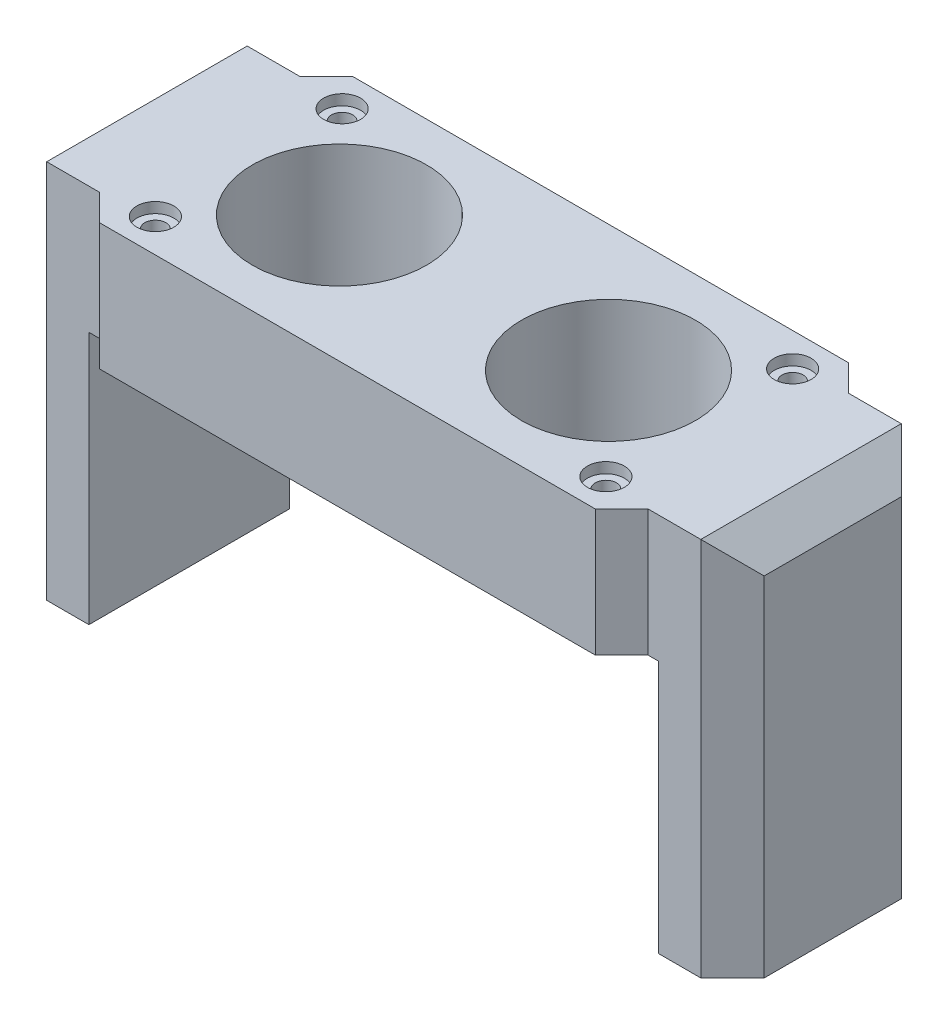
SolidWorks part; units mm, degrees
ref_plane "Front Plane" through (0, 0, 0) normal (0, 0, 1) x (1, 0, 0)
ref_plane "Top Plane" through (0, 0, 0) normal (0, 1, 0) x (1, 0, 0)
ref_plane "Right Plane" through (0, 0, 0) normal (1, 0, 0) x (0, 0, -1)
sketch "Sketch1" plane through (0, 0, 0) normal (0, 1, 0) x (1, 0, 0)
  line L0 (-12.75, 0) -> (12.75, 0) construction
  line L1 (-26, 12) -> (26, 12)
  line L2 (-26, 12) -> (-26, -12)
  line L3 (-26, -12) -> (26, -12)
  line L4 (26, 12) -> (26, -12)
  line L5 (-26, 12) -> (26, -12) construction
  line L6 (-26, -12) -> (26, 12) construction
  circle A0 centre (12.75, 0) radius 8.25
  circle A1 centre (-12.75, 0) radius 8.25
  point P0 (0, 0)
  point P9 (0, 0)
  dimension "D3" = 16.5
  dimension "D1" = 52
  dimension "D2" = 24
  dimension "D4" = 25.5
extrude "Boss-Extrude1" add sketch "Sketch1" along normal blind 12
sketch "Sketch2" plane through (0, 12, 0) normal (0, 1, 0) x (1, 0, 0)
  line L1 (-21.35, 8.85) -> (21.35, 8.85) construction
  line L2 (-21.35, 8.85) -> (-21.35, -8.85) construction
  line L3 (-21.35, -8.85) -> (21.35, -8.85) construction
  line L4 (21.35, 8.85) -> (21.35, -8.85) construction
  line L5 (-21.35, 8.85) -> (21.35, -8.85) construction
  line L6 (-21.35, -8.85) -> (21.35, 8.85) construction
  circle A0 centre (-21.35, 8.85) radius 1
  circle A1 centre (21.35, 8.85) radius 1
  circle A2 centre (21.35, -8.85) radius 1
  circle A3 centre (-21.35, -8.85) radius 1
  point P0 (0, 0)
  dimension "D3" = 2
  dimension "D1" = 17.7
  dimension "D2" = 42.7
extrude "Cut-Extrude1" cut sketch "Sketch2" against normal through all
sketch "Sketch3" plane through (0, 12, 0) normal (0, 1, 0) x (1, 0, 0)
  circle A20 centre (-21.35, 8.85) radius 1.75
  circle A21 centre (21.35, 8.85) radius 1.75
  circle A23 centre (21.35, -8.85) radius 1.75
  circle A24 centre (-21.35, -8.85) radius 1.75
  dimension "D1" = 3.5
extrude "Cut-Extrude2" cut sketch "Sketch3" against normal blind 1
sketch "Sketch4" plane through (0, 0, 0) normal (0, -1, 0) x (1, 0, 0)
  line L0 (26, -12) -> (-26, -12) construction
  line L1 (-6, -12) -> (6, -12)
  line L2 (-6, -12) -> (-6, -5)
  line L3 (-6, -5) -> (6, -5)
  line L4 (6, -12) -> (6, -5)
  line L5 (0, -5) -> (0, 0)
  line M14 (-26, -12) -> (26, -12)
  dimension "D1" = 7
  dimension "D2" = 12
extrude "Cut-Extrude3" cut sketch "Sketch4" against normal blind 5 contours L4 L3 L2 M14
fillet "Fillet3" radius 0.5 5 edges at (-6, 5, -8.5) (6, 5, -8.5) (6, 2.5, -5) (0, 5, -5) (-6, 2.5, -5)
chamfer "Chamfer1" distance 2.5 4 edges at (26, 6, 12) (26, 6, -12) (-26, 6, -12) (-26, 6, 12)
sketch "Sketch5" plane through (-26, 0, 0) normal (-1, 0, 0) x (0, 0, 1)
  line L4 (9.5, 12) -> (-9.5, 12)
  line L5 (-9.5, 12) -> (-9.5, 0)
  line L6 (-9.5, 0) -> (9.5, 0)
  line L7 (9.5, 0) -> (9.5, 12)
  line L8 (9.5, 12) -> (-9.5, 12)
  line L9 (-9.5, 12) -> (-9.5, 0)
  line L10 (-9.5, 0) -> (9.5, 0)
  line L11 (9.5, 0) -> (9.5, 12)
  dimension "D1" = 0
extrude "Boss-Extrude2" add sketch "Sketch5" along normal blind 8
sketch "Sketch6" plane through (0, 0, 0) normal (0, -1, 0) x (1, 0, 0)
  line L0 (-34, 9.5) -> (-34, -9.5)
  line L1 (-34, 9.5) -> (-26, 9.5) construction
  line L2 (-34, -9.5) -> (-34, 9.5) construction
  line L3 (-34, -9.5) -> (-27, -9.5)
  line L4 (-34, -9.5) -> (-26, -9.5) construction
  line L5 (-27, -9.5) -> (-27, 9.5)
  line L6 (-27, 9.5) -> (-34, 9.5)
  dimension "D1" = 7
extrude "Boss-Extrude3" add sketch "Sketch6" along normal blind 24 contours L6 L0 L3 L5
chamfer "Chamfer2" distance 3 angle 45 3 edges at (-34, -6, -9.5) (-34, -6, 9.5) (-34, 12, 0)
mirror "Mirror1" about plane through (0, 0, 0) normal (1, 0, 0) of "Boss-Extrude2", "Boss-Extrude3", "Chamfer2"
